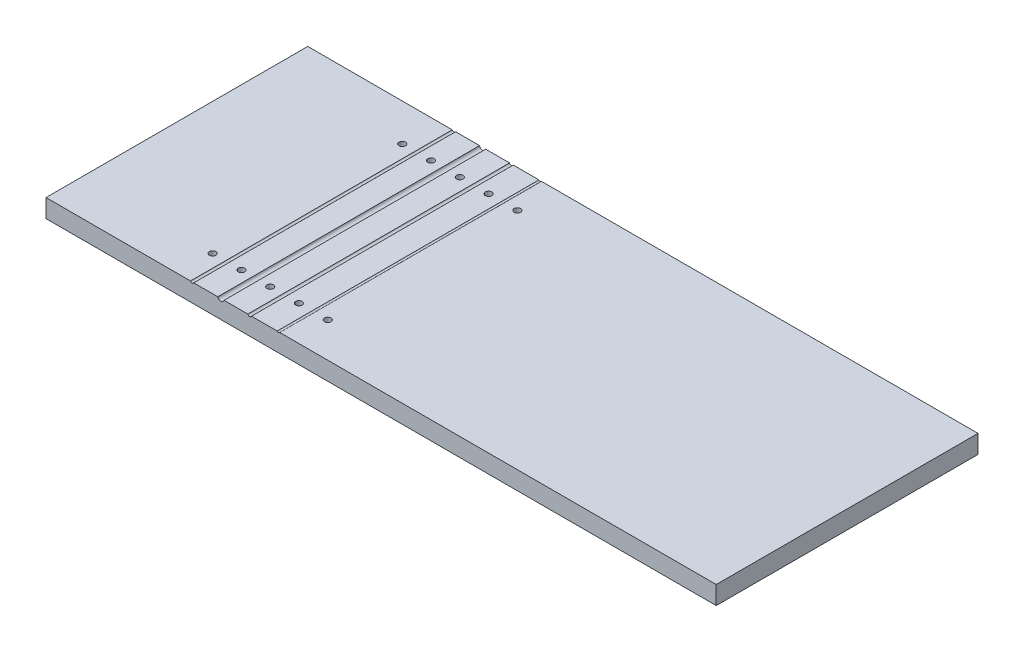
SolidWorks part; units mm, degrees
ref_plane "Front Plane" through (0, 0, 0) normal (0, 0, 1) x (1, 0, 0)
ref_plane "Top Plane" through (0, 0, 0) normal (0, 1, 0) x (1, 0, 0)
ref_plane "Right Plane" through (0, 0, 0) normal (1, 0, 0) x (0, 0, -1)
sketch "Sketch1" plane through (0, 0, 0) normal (0, 1, 0) x (1, 0, 0)
  line L1 (-6.3794, 85.4337) -> (226.6206, 85.4337)
  line L2 (-6.3794, 85.4337) -> (-6.3794, -5.5663)
  line L3 (-6.3794, -5.5663) -> (226.6206, -5.5663)
  line L4 (226.6206, 85.4337) -> (226.6206, -5.5663)
  dimension "D1" = 91
  dimension "D2" = 233
extrude "Boss-Extrude1" add sketch "Sketch1" along normal blind 6.35
sketch "Sketch2" plane through (0, 0, 5.5663) normal (0, 0, 1) x (1, 0, 0)
  line L0 (54.4206, 6.6) -> (81.4623, 6.6) construction
  line L3 (44.4206, 6.6) -> (54.4206, 6.6) construction
  line L4 (-6.3794, 6.35) -> (226.6206, 6.35) construction
  circle A0 centre (44.4206, 6.6) radius 0.6223
  circle A1 centre (54.4206, 6.6) radius 1.1
  circle A2 centre (64.4206, 6.6) radius 0.6858
  circle A3 centre (74.4206, 6.6) radius 0.5
  dimension "D1" = 1.2446
  dimension "D3" = 2.2
  dimension "D6" = 1.3716
  dimension "D7" = 1
  dimension "D2" = 0.25
  dimension "D4" = 10
  dimension "D5" = 50.8
  dimension "D8" = 10
  dimension "D9" = 10
extrude "Cut-Extrude1" cut sketch "Sketch2" against normal through all
sketch "Sketch3" plane through (0, 6.35, 0) normal (0, 1, 0) x (1, 0, 0)
  line L0 (49.4206, 72.4912) -> (49.4206, 6.5743) construction
  line L1 (39.4206, 72.4912) -> (59.4206, 72.4912) construction
  line L2 (39.4206, 72.4912) -> (39.4206, 6.5743) construction
  line L3 (39.4206, 6.5743) -> (59.4206, 6.5743) construction
  line L4 (59.4206, 72.4912) -> (59.4206, 6.5743) construction
  line L5 (44.9905, 85.4337) -> (43.8507, 85.4337) construction
  line L6 (55.4918, 85.4337) -> (53.3494, 85.4337) construction
  line L7 (44.9905, 85.4337) -> (43.8507, 85.4337) construction
  line L8 (55.4918, 85.4337) -> (53.3494, 85.4337) construction
  line L9 (44.4206, 85.4337) -> (44.4206, -5.5825) construction
  line L10 (54.4206, 85.4337) -> (54.4206, -5.5825) construction
  line L11 (59.4206, 72.4912) -> (79.4206, 72.4912) construction
  line L12 (69.4206, 72.4912) -> (69.4206, 6.5743) construction
  line L13 (59.4206, 6.5743) -> (79.4206, 6.5743) construction
  line L14 (65.0592, 85.4337) -> (63.782, 85.4337) construction
  line L15 (74.8536, 85.4337) -> (73.9876, 85.4337) construction
  line L16 (65.0592, 85.4337) -> (63.782, 85.4337) construction
  line L17 (74.8536, 85.4337) -> (73.9876, 85.4337) construction
  line L18 (64.4206, 85.4337) -> (64.4206, -5.5663) construction
  line L19 (74.4206, 85.4337) -> (74.4206, -5.5663) construction
  line L20 (79.4206, 72.4912) -> (79.4206, 6.5743) construction
  point P10 (44.4206, 85.4337)
  point P11 (54.4206, 85.4337)
  dimension "D1" = 20
  dimension "D2" = 5
  dimension "D3" = 5
  dimension "D4" = 5
hole_wizard "#4-40 Tapped Hole1" positions "Sketch5" profile "Sketch4" tap size "#4-40" standard "ANSI Inch" end condition through all
sketch "Sketch5" plane through (0, 6.35, 0) normal (0, 1, 0) x (1, 0, 0)
  point P0 (39.4206, 72.4912)
  point P3 (59.4206, 72.4912)
  point P6 (49.4206, 72.4912)
  point P9 (49.4206, 6.5743)
  point P12 (39.4206, 6.5743)
  point P15 (59.4206, 6.5743)
  point P18 (69.4206, 72.4912)
  point P21 (79.4206, 72.4912)
  point P24 (69.4206, 6.5743)
  point P27 (79.4206, 6.5743)
sketch "Sketch4" plane through (39.4206, 6.35, -72.4912) normal (1, 0, 0) x (0, 0, 1)
  line L0 (0, 0) -> (0, 6.35)
  line L1 (0, 6.35) -> (1.1303, 6.35)
  line L2 (1.1303, 6.35) -> (1.1303, 0)
  line L5 (1.1303, 0) -> (0, 0)
  line L11 (0, -6.35) -> (0, 107.95) construction
  dimension "Thru Tap Drill Dia." = 2.2606
  dimension "Thru Tap Drill Depth" = 6.35
cosmetic thread "Hole Thread1" parameters "D2"=2.8448
cosmetic thread "Hole Thread2" parameters "D2"=2.8448
cosmetic thread "Hole Thread3" parameters "D2"=2.8448
cosmetic thread "Hole Thread4" parameters "D2"=2.8448
cosmetic thread "Hole Thread5" parameters "D2"=2.8448
cosmetic thread "Hole Thread6" parameters "D2"=2.8448
cosmetic thread "Hole Thread7" parameters "D2"=2.8448
cosmetic thread "Hole Thread8" parameters "D2"=2.8448
cosmetic thread "Hole Thread9" parameters "D2"=2.8448
cosmetic thread "Hole Thread10" parameters "D2"=2.8448
